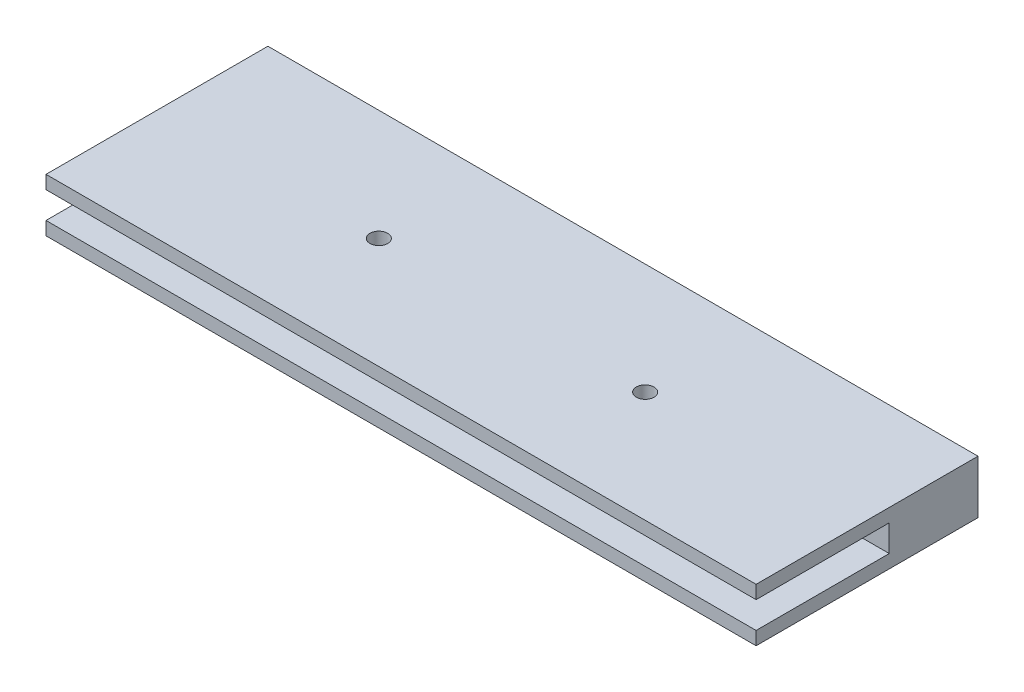
SolidWorks part; units mm, degrees
ref_plane "Alzado" through (0, 0, 0) normal (0, 0, 1) x (1, 0, 0)
ref_plane "Planta" through (0, 0, 0) normal (0, 1, 0) x (1, 0, 0)
ref_plane "Vista lateral" through (0, 0, 0) normal (1, 0, 0) x (0, 0, -1)
sketch "Croquis1" plane through (0, 0, 0) normal (0, 0, 1) x (1, 0, 0)
  line L1 (0, 0) -> (80, 0)
  line L2 (0, 0) -> (0, 6)
  line L3 (0, 6) -> (80, 6)
  line L4 (80, 0) -> (80, 6)
  dimension "D1" = 6
  dimension "D2" = 80
extrude "Saliente-Extruir4" add sketch "Croquis1" along normal blind 10
sketch "Croquis5" plane through (0, 0, 10) normal (0, 0, 1) x (1, 0, 0)
  line L10 (0, 6) -> (80, 6)
  line L11 (0, 6) -> (0, 0)
  line L12 (0, 0) -> (80, 0)
  line L13 (80, 6) -> (80, 0)
extrude "Saliente-Extruir6" add sketch "Croquis5" along normal blind 10
sketch "Croquis7" plane through (0, 0, 20) normal (0, 0, 1) x (1, 0, 0)
  line L0 (80, 0) -> (80, 6) construction
  line L1 (0, 6) -> (80, 6)
  line L2 (0, 6) -> (0, 4.5)
  line L3 (0, 4.5) -> (80, 4.5)
  line L4 (80, 6) -> (80, 4.5)
  line L6 (0, 0) -> (80, 0)
  line L7 (0, 0) -> (0, 1.5)
  line L8 (0, 1.5) -> (80, 1.5)
  line L9 (80, 0) -> (80, 1.5)
extrude "Saliente-Extruir7" add sketch "Croquis7" along normal blind 10
sketch "Croquis9" plane through (0, 0, 0) normal (-1, 0, 0) x (0, 0, 1)
  line L1 (20, 4.5) -> (15, 4.5)
  line L2 (20, 4.5) -> (20, 1.5)
  line L3 (20, 1.5) -> (15, 1.5)
  line L4 (15, 4.5) -> (15, 1.5)
extrude "Cortar-Extruir3" cut sketch "Croquis9" against normal blind 80 contours L2 L1 L4 L3
sketch "Croquis12" plane through (0, 0, 0) normal (0, 0, -1) x (-1, 0, 0)
  line L1 (-80, 6) -> (0, 6)
  line L2 (-80, 6) -> (-80, 0)
  line L3 (-80, 0) -> (0, 0)
  line L4 (0, 6) -> (0, 0)
extrude "Cortar-Extruir4" cut sketch "Croquis12" against normal blind 10
sketch "Croquis13" plane through (0, 0, 10) normal (0, 0, -1) x (-1, 0, 0)
  line L1 (-80, 6) -> (0, 6)
  line L2 (-80, 6) -> (-80, 0)
  line L3 (-80, 0) -> (0, 0)
  line L4 (0, 6) -> (0, 0)
extrude "Saliente-Extruir8" add sketch "Croquis13" along normal blind 5
sketch "Croquis14" plane through (0, 6, 0) normal (0, 1, 0) x (1, 0, 0)
  line L0 (0, -5) -> (0, -30) construction
  line L1 (80, -5) -> (80, -30) construction
  circle A0 centre (20, -17.5) radius 1
  circle A1 centre (60, -17.5) radius 1
extrude "Cortar-Extruir5" cut sketch "Croquis14" against normal blind 25
sketch "Croquis15" plane through (0, 6, 0) normal (0, 1, 0) x (1, 0, 0)
  circle A0 centre (20, -17.5) radius 1
  circle A1 centre (60, -17.5) radius 1
extrude "Saliente-Extruir9" add sketch "Croquis15" against normal blind 1
sketch "Croquis16" plane through (0, 0, 0) normal (0, -1, 0) x (1, 0, 0)
  circle A0 centre (20, 17.5) radius 1
  circle A1 centre (60, 17.5) radius 1
extrude "Saliente-Extruir10" add sketch "Croquis16" against normal blind 1
sketch "Croquis17" plane through (0, 6, 0) normal (0, 1, 0) x (1, 0, 0)
  line L0 (0, -17.5) -> (80, -17.5) construction
  line L1 (0, -30) -> (0, -5) construction
  line L2 (80, -30) -> (80, -5) construction
  line L3 (40, -5) -> (40, -30) construction
  line L4 (0, -5) -> (80, -5) construction
  line L5 (80, -30) -> (0, -30) construction
  line L6 (40, -30) -> (25, -30) construction
  line L7 (25, -30) -> (25, -17.5) construction
  line L8 (40, -30) -> (55, -30) construction
  line L9 (55, -30) -> (55, -17.5) construction
  circle A0 centre (25, -17.5) radius 1
  circle A1 centre (55, -17.5) radius 1
extrude "Cortar-Extruir6" cut sketch "Croquis17" against normal blind 25 and the other way through all
